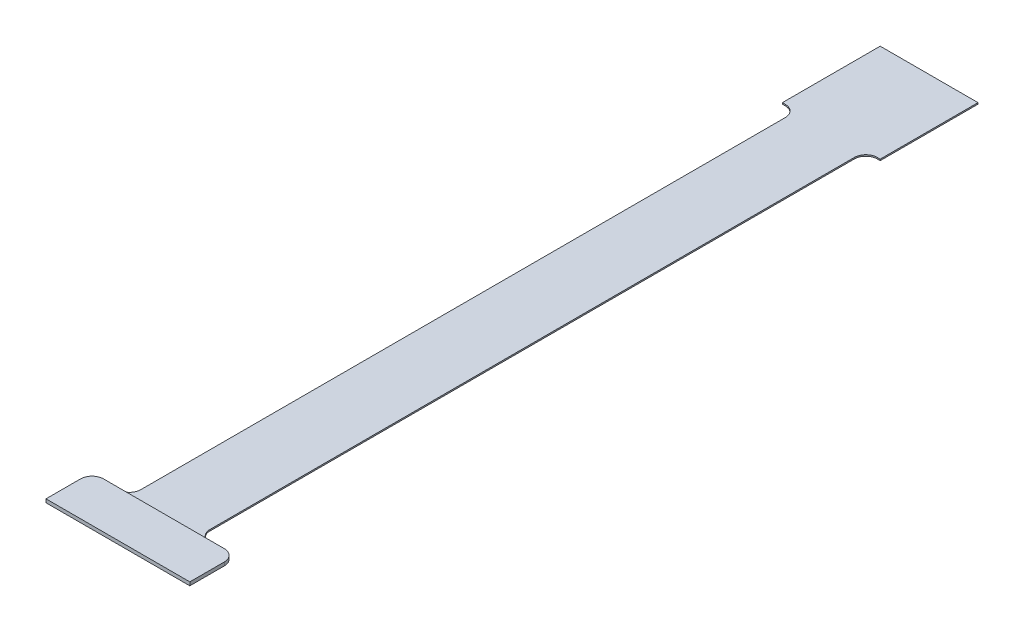
SolidWorks part; units mm, degrees
material "Copper"
ref_plane "Front Plane" through (0, 0, 0) normal (0, 0, 1) x (1, 0, 0)
ref_plane "Top Plane" through (0, 0, 0) normal (0, 1, 0) x (1, 0, 0)
ref_plane "Right Plane" through (0, 0, 0) normal (1, 0, 0) x (0, 0, -1)
sketch "Sketch1" plane through (0, 0, 0) normal (0, 1, 0) x (1, 0, 0)
  line L0 (-4.25, 0) -> (4.25, 0)
  line L1 (-4.25, 0) -> (-4.25, -8.5)
  line L2 (-4.25, -8.5) -> (-3, -8.5)
  line L3 (-3, -8.5) -> (-3, -66.5)
  line L4 (-3, -66.5) -> (-6.25, -66.5)
  line L5 (-6.25, -66.5) -> (-6.25, -70.5)
  line L6 (-6.25, -70.5) -> (6.25, -70.5)
  line L7 (6.25, -70.5) -> (6.25, -66.5)
  line L8 (6.25, -66.5) -> (3, -66.5)
  line L9 (3, -66.5) -> (3, -8.5)
  line L10 (3, -8.5) -> (4.25, -8.5)
  line L11 (4.25, -8.5) -> (4.25, 0)
  point P9 (6.25, -50.2293)
  dimension "D1" = 8.5
  dimension "D2" = 8.5
  dimension "D3" = 6
  dimension "D4" = 4
  dimension "D5" = 12.5
  dimension "D6" = 70.5
extrude "Boss-Extrude1" add sketch "Sketch1" along normal blind 0.12
sketch "Sketch2" plane through (0, 0.12, 0) normal (0, 1, 0) x (1, 0, 0)
  line L1 (-6.25, -66.5) -> (6.25, -66.5)
  line L2 (-6.25, -66.5) -> (-6.25, -70.5)
  line L3 (-6.25, -70.5) -> (6.25, -70.5)
  line L4 (6.25, -66.5) -> (6.25, -70.5)
extrude "Boss-Extrude2" add sketch "Sketch2" along normal offset from surface (0.18 mm away) 0.3 up to face at (0, 0, 36.75)
fillet "Fillet1" radius 1 6 edges at (-6.25, 0.15, 66.5) (6.25, 0.15, 66.5) (3, 0.06, 66.5) (-3, 0.06, 66.5) (-3, 0.06, 8.5) (3, 0.06, 8.5)
